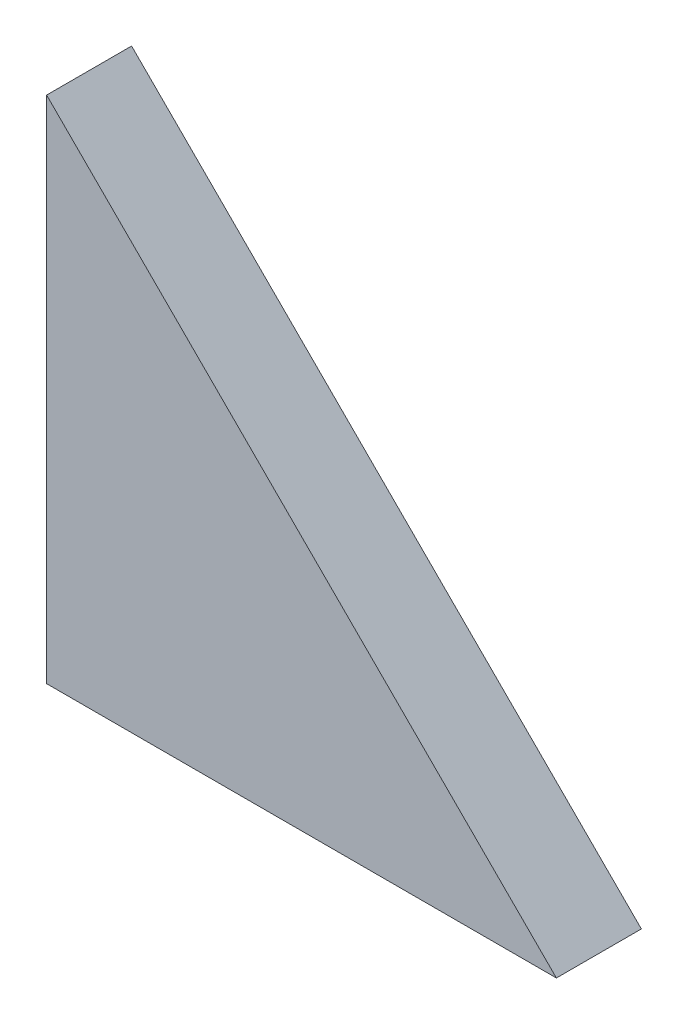
SolidWorks part; units mm, degrees
ref_plane "Front Plane" through (0, 0, 0) normal (0, 0, 1) x (1, 0, 0)
ref_plane "Top Plane" through (0, 0, 0) normal (0, 1, 0) x (1, 0, 0)
ref_plane "Right Plane" through (0, 0, 0) normal (1, 0, 0) x (0, 0, -1)
sketch "Sketch1" plane through (0, 0, 0) normal (0, 0, 1) x (1, 0, 0)
  line L0 (0, 60) -> (60, 0)
  line L1 (0, 0) -> (60, 0)
  line L2 (0, 0) -> (0, 60)
  dimension "D1" = 60
  dimension "D2" = 60
extrude "Boss-Extrude1" add sketch "Sketch1" along normal blind 10
